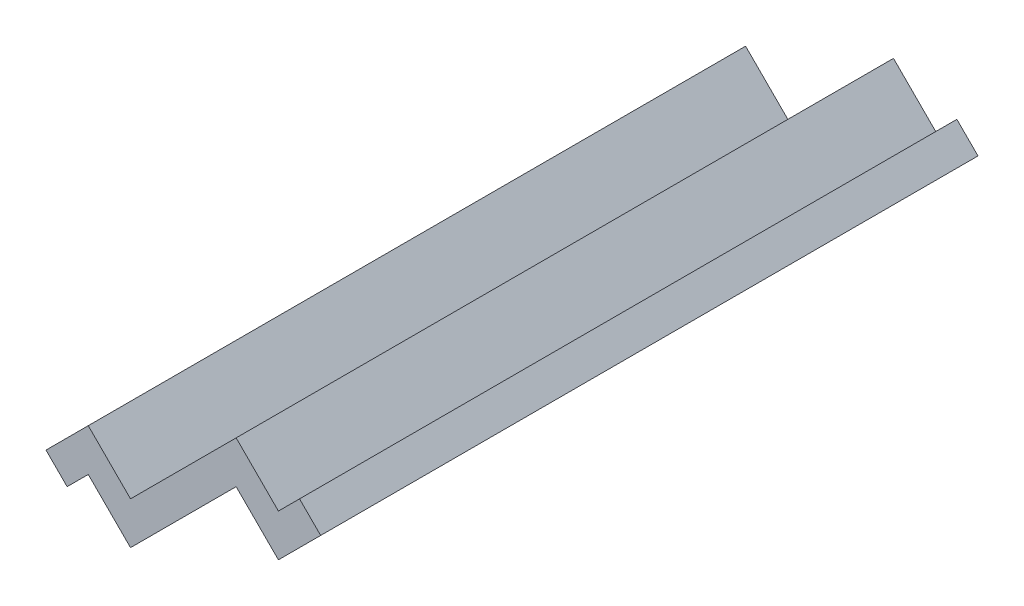
SolidWorks part; units mm, degrees
ref_plane "前视基准面" through (0, 0, 0) normal (0, 0, 1) x (1, 0, 0)
ref_plane "上视基准面" through (0, 0, 0) normal (0, 1, 0) x (1, 0, 0)
ref_plane "右视基准面" through (0, 0, 0) normal (1, 0, 0) x (0, 0, -1)
sketch "草图1" plane through (0, 0, 0) normal (0, 0, 1) x (1, 0, 0)
  line L0 (0, 0) -> (-10.6066, -10.6066)
  line L2 (-17.6777, -3.5355) -> (0, 14.1421)
  line L6 (0, 0) -> (17.6777, 17.6777)
  line L8 (10.6066, 24.7487) -> (0, 14.1421)
  line L9 (0, 0) -> (0, -32.547) construction
  line L11 (-31.8198, 10.6066) -> (-17.6777, -3.5355)
  line L12 (31.8198, 17.6777) -> (17.6777, 31.8198)
  line L13 (17.6777, 31.8198) -> (10.6066, 24.7487)
  line L14 (17.6777, 17.6777) -> (31.8198, 3.5355)
  line L17 (-31.8198, -3.5355) -> (-17.6777, -17.6777)
  line L18 (-17.6777, -17.6777) -> (-10.6066, -10.6066)
  line L20 (31.8198, 17.6777) -> (38.8909, 24.7487)
  line L21 (38.8909, 24.7487) -> (45.9619, 17.6777)
  line L23 (31.8198, 3.5355) -> (45.9619, 17.6777)
  line L24 (-31.8198, -3.5355) -> (-38.8909, -10.6066)
  line L25 (-38.8909, -10.6066) -> (-45.9619, -3.5355)
  line L26 (-45.9619, -3.5355) -> (-31.8198, 10.6066)
  point P5 (14.1421, 28.2843)
  dimension "D1" = 15
  dimension "D2" = 15
  dimension "D3" = 45
  dimension "D4" = 10
  dimension "D5" = 10
  dimension "D6" = 10
  dimension "D7" = 10
  dimension "D8" = 10
  dimension "D9" = 20
  dimension "D10" = 20
  dimension "D11" = 10
  dimension "D12" = 10
extrude "凸台-拉伸1" add sketch "草图1" along normal blind 220
